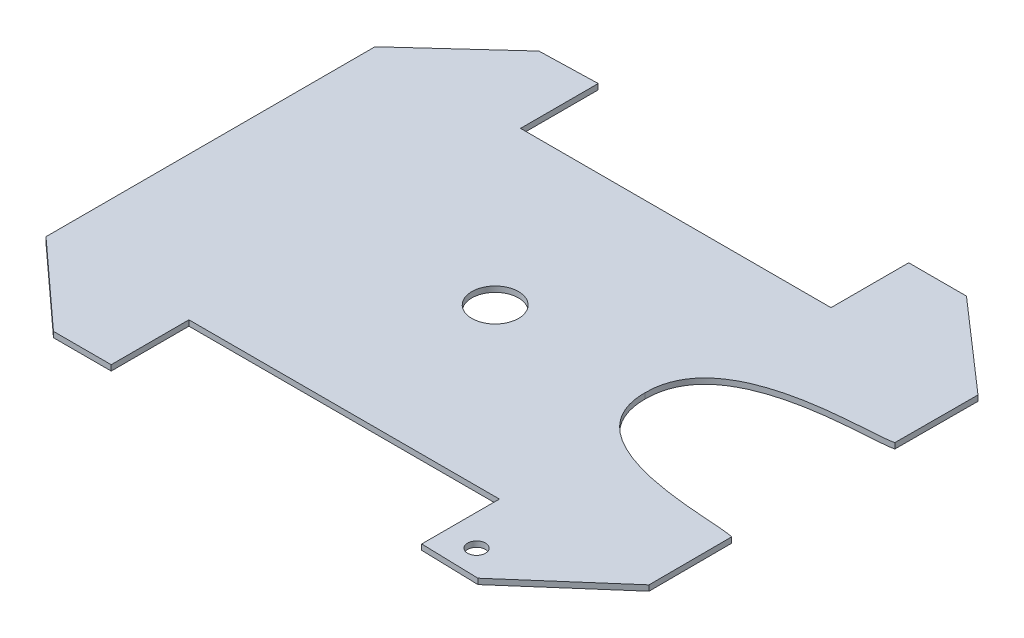
SolidWorks part; units mm, degrees
ref_plane "Спереди" through (0, 0, 0) normal (0, 0, 1) x (1, 0, 0)
ref_plane "Сверху" through (0, 0, 0) normal (0, 1, 0) x (1, 0, 0)
ref_plane "Справа" through (0, 0, 0) normal (1, 0, 0) x (0, 0, -1)
sketch "Эскиз1" plane through (0, 0, 0) normal (0, 1, 0) x (1, 0, 0)
  line L1 (-269.7922, 73.2626) -> (-269.7922, -223.012)
  line L2 (139.0683, -293.4928) -> (191.0683, -294.8909)
  line L3 (-140.5865, 145.1415) -> (-192.5865, 143.7434)
  line L4 (139.0683, -223.4928) -> (139.0683, -293.4928)
  line L5 (139.0683, 145.1415) -> (191.0683, 145.1415)
  line L6 (-140.5865, 75.1415) -> (-140.5865, 145.1415)
  line L7 (-0.7591, -12.2026) -> (-0.7591, 227.1905) construction
  line L8 (273.3416, 73.2626) -> (273.1017, -1.3674)
  line L9 (-140.5865, -223.4928) -> (139.0683, -223.4928)
  line L10 (139.0683, 75.1415) -> (139.0683, 145.1415)
  line L11 (-140.5865, 75.1415) -> (139.0683, 75.1415)
  line L12 (-140.5865, -223.4928) -> (-140.5865, -293.4928)
  line L13 (-140.5865, -293.4928) -> (-192.5865, -293.4928)
  line L14 (273.3416, -223.012) -> (273.1017, -148.382)
  line L17 (-326.8393, -74.8747) -> (107.7018, -74.8747) construction
  line L22 (-269.7922, 73.2626) -> (-192.5865, 143.7434)
  line L23 (-269.7922, -223.012) -> (-192.5865, -293.4928)
  line L24 (-263.7922, 73.2626) -> (-387.0064, 73.2626) construction
  line L25 (-269.7922, -223.012) -> (-392.2998, -223.012) construction
  line L26 (273.3416, -223.012) -> (191.0683, -294.8909)
  line L27 (273.3416, 73.2626) -> (191.0683, 145.1415)
  spline S0 degree 3 poles (273.1017, -1.3674) (253.0562, -7.0064) (121.2308, 1.865) (121.6624, -74.8747) knots 0 0 0 0 1 1 1 1
  spline S2 degree 3 poles (273.1017, -148.382) (253.0562, -142.7431) (121.2308, -151.6145) (121.6624, -74.8747) knots 0 0 0 0 1 1 1 1
extrude "Вытянуть1" add sketch "Эскиз1" along normal blind 5
sketch "Эскиз2" plane through (0, 5, 0) normal (0, 1, 0) x (-1, 0, 0)
  circle A0 centre (14.23, 74.0267) radius 21
extrude "Вырез-Вытянуть1" cut sketch "Эскиз2" against normal through all
sketch "Sketch1" plane through (0, 5, 0) normal (0, 1, 0) x (1, 0, 0)
  circle A0 centre (167.053, -272.0659) radius 8
extrude "Cut-Extrude1" cut sketch "Sketch1" against normal through all
